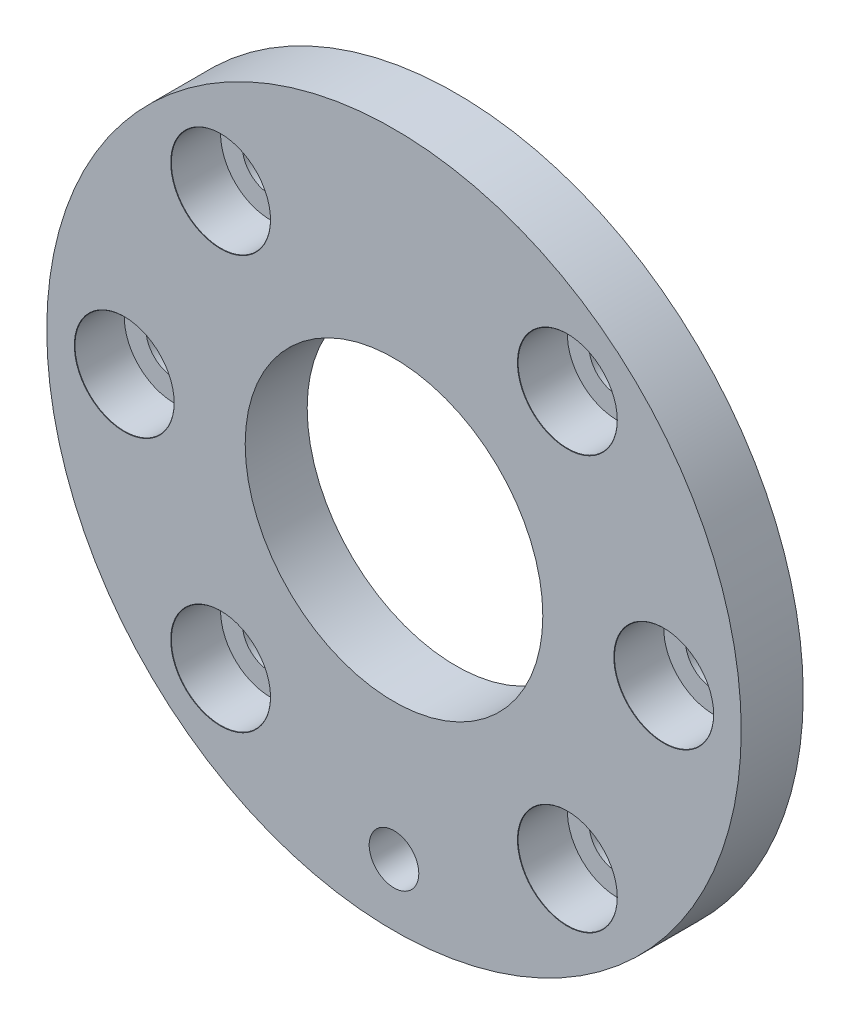
SolidWorks part; units mm, degrees
ref_plane "前视基准面" through (0, 0, 0) normal (0, 0, 1) x (1, 0, 0)
ref_plane "上视基准面" through (0, 0, 0) normal (0, 1, 0) x (1, 0, 0)
ref_plane "右视基准面" through (0, 0, 0) normal (1, 0, 0) x (0, 0, -1)
sketch "草图1" plane through (0, 0, 0) normal (0, 0, 1) x (1, 0, 0)
  circle A2 centre (0, 0) radius 28
  circle A4 centre (0, 0) radius 12
extrude "凸台-拉伸1" add sketch "草图1" along normal blind 5
hole_wizard "M4 六角凹头盖的柱孔1" positions "3D草图1" profile "草图3" counterbore size "M4" standard "BSI" end condition through all
sketch3d "3D草图1"
  line L0 (0, 0, 0) -> (-21.75, 0, 0)
  arc A1 (-21.75, 0, 0) -> (-13.9806, 16.6615, 0) centre (0, 0, 0) cw
  point P12 (0, 0, -21.75)
  point P13 (-13.9806, 16.6615, 0)
  point P17 (-13.9806, 16.6615, 0)
  point P19 (-13.9806, 16.6615, 0)
  point P21 (-13.9806, 16.6615, 5)
  point P23 (13.9806, -16.6615, 5)
  point P25 (-13.9806, -16.6615, 5)
  point P27 (13.9806, 16.6615, 5)
  point P44 (-21.75, 0, 5)
  point P46 (21.75, 0, 5)
sketch "草图3" plane through (21.75, 0, 5) normal (1, 0, 0) x (0, -1, 0)
  line L0 (0, 0) -> (0, 5)
  line L1 (0, 5) -> (2.25, 5)
  line L3 (2.25, 5) -> (2.25, 4)
  line L4 (4, 4) -> (2.25, 4)
  line L5 (4, 4) -> (4, 0.0241)
  line L6 (4, 0.0241) -> (4.025, 0)
  line L7 (4.025, 0) -> (0, 0)
  line L8 (-4, 0.0241) -> (-4.025, 0) construction
  line L11 (0, -6.35) -> (0, 107.95) construction
  dimension "通孔孔直径" = 4.5
  dimension "通孔孔深度" = 5
  dimension "柱形沉头孔直径" = 8
  dimension "柱形沉头孔深度" = 4
  dimension "近端锥形沉头孔直径" = 8.05
  dimension "近端锥形沉头孔角度" = 92
sketch "草图4" plane through (0, 0, 0) normal (0, 0, 1) x (1, 0, 0)
  circle A0 centre (0, -23) radius 2
extrude "切除-拉伸1" cut sketch "草图4" along normal blind 10
